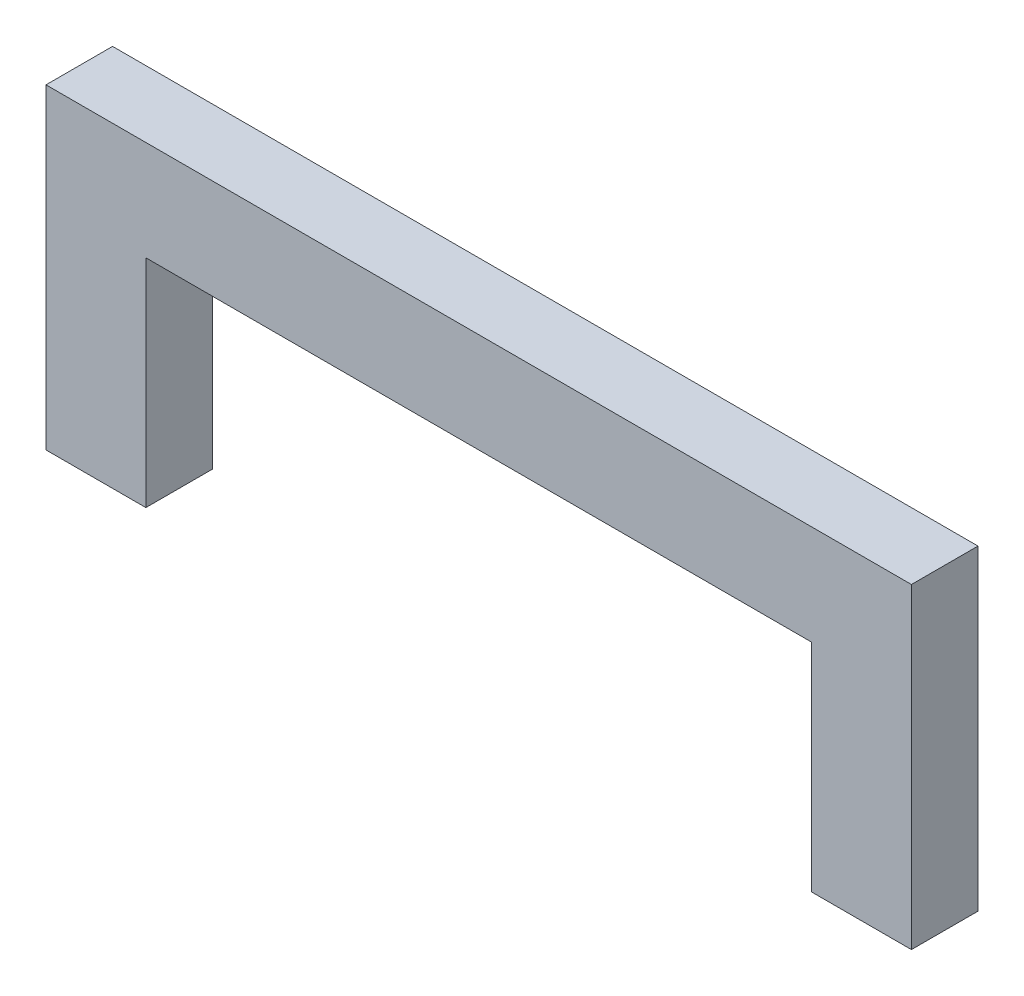
SolidWorks part; units mm, degrees
ref_plane "Front Plane" through (0, 0, 0) normal (0, 0, 1) x (1, 0, 0)
ref_plane "Top Plane" through (0, 0, 0) normal (0, 1, 0) x (1, 0, 0)
ref_plane "Right Plane" through (0, 0, 0) normal (1, 0, 0) x (0, 0, -1)
sketch "Sketch1" plane through (0, 0, 0) normal (0, 0, 1) x (1, 0, 0)
  line L8 (-63.5, 0) -> (-82.55, 0)
  line L9 (-82.55, 0) -> (-82.55, 60.325)
  line L10 (-82.55, 60.325) -> (82.55, 60.325)
  line L12 (63.5, 41.275) -> (-63.5, 41.275)
  line L13 (-63.5, 41.275) -> (-63.5, 0)
  line L14 (0, -56.9499) -> (0, 148.1766) construction
  line L15 (0, 41.275) -> (-82.55, 60.325) construction
  line L16 (63.5, 0) -> (82.55, 0)
  line L17 (82.55, 0) -> (82.55, 60.325)
  line L18 (63.5, 41.275) -> (63.5, 0)
  point P9 (-41.275, 50.8)
  point P10 (0, 0)
  point P12 (0, 60.325)
  point P13 (0, 41.275)
  point P17 (0, 60.325)
  dimension "D1" = 19.05
  dimension "D2" = 19.05
  dimension "D3" = 50.8
  dimension "D4" = 82.55
extrude "Boss-Extrude1" add sketch "Sketch1" along normal mid plane 12.7
